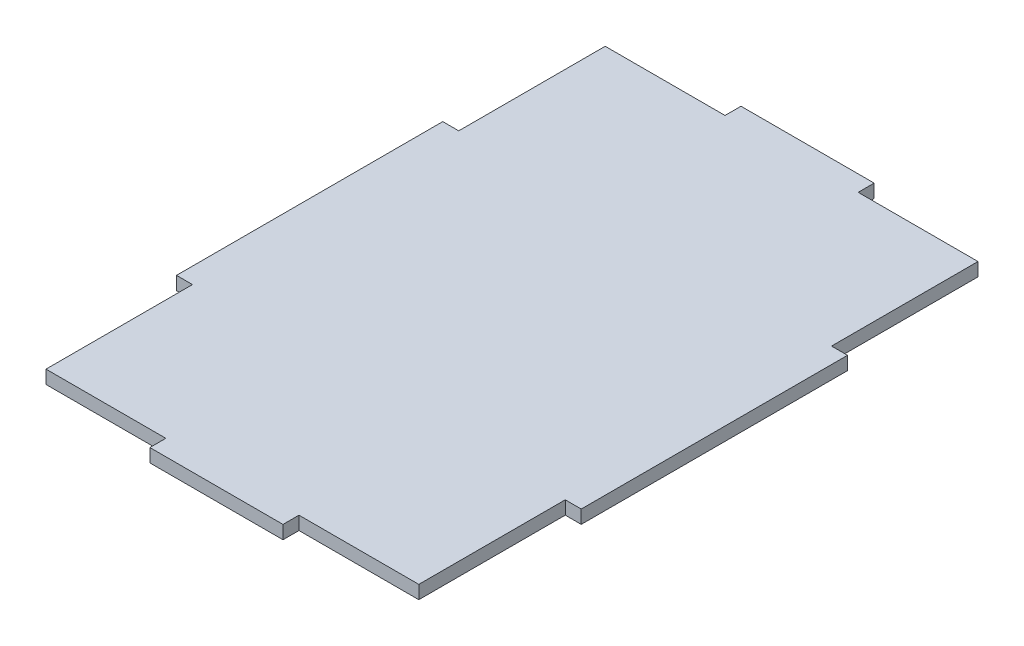
SolidWorks part; units mm, degrees
ref_plane "Front Plane" through (0, 0, 0) normal (0, 0, 1) x (1, 0, 0)
ref_plane "Top Plane" through (0, 0, 0) normal (0, 1, 0) x (1, 0, 0)
ref_plane "Right Plane" through (0, 0, 0) normal (1, 0, 0) x (0, 0, -1)
sketch "Sketch2" plane through (0, 0, 0) normal (0, 1, 0) x (1, 0, 0)
  line L0 (-44.45, 66.675) -> (-44.45, 31.75)
  line L1 (44.45, 66.675) -> (44.45, 31.75)
  line L2 (-44.45, -66.675) -> (-15.875, -66.675)
  line L3 (0, 70.485) -> (0, -70.485) construction
  line L4 (-44.45, -31.75) -> (-44.45, -66.675)
  line L5 (44.45, 66.675) -> (15.875, 66.675)
  line L6 (-48.26, 0) -> (48.26, 0) construction
  line L7 (-15.875, 66.675) -> (-15.875, 70.485)
  line L8 (-15.875, 70.485) -> (15.875, 70.485)
  line L9 (15.875, 66.675) -> (15.875, 70.485)
  line L11 (-44.45, 31.75) -> (-48.26, 31.75)
  line L12 (44.45, -31.75) -> (44.45, -66.675)
  line L13 (-44.45, -31.75) -> (-48.26, -31.75)
  line L14 (-48.26, 31.75) -> (-48.26, -31.75)
  line L15 (44.45, 31.75) -> (48.26, 31.75)
  line L16 (15.875, -66.675) -> (44.45, -66.675)
  line L17 (44.45, -31.75) -> (48.26, -31.75)
  line L18 (48.26, 31.75) -> (48.26, -31.75)
  line L22 (-15.875, -66.675) -> (-15.875, -70.485)
  line L23 (-15.875, -70.485) -> (15.875, -70.485)
  line L24 (15.875, -66.675) -> (15.875, -70.485)
  line L25 (-15.875, 66.675) -> (-44.45, 66.675)
  dimension "D1" = 88.9
  dimension "D2" = 133.35
  dimension "D3" = 3.81
  dimension "D4" = 31.75
  dimension "D5" = 3.81
  dimension "D6" = 3.81
  dimension "D7" = 63.5
  dimension "D8" = 3.81
  dimension "D9" = 31.75
extrude "Boss-Extrude1" add sketch "Sketch2" along normal blind 3.175
